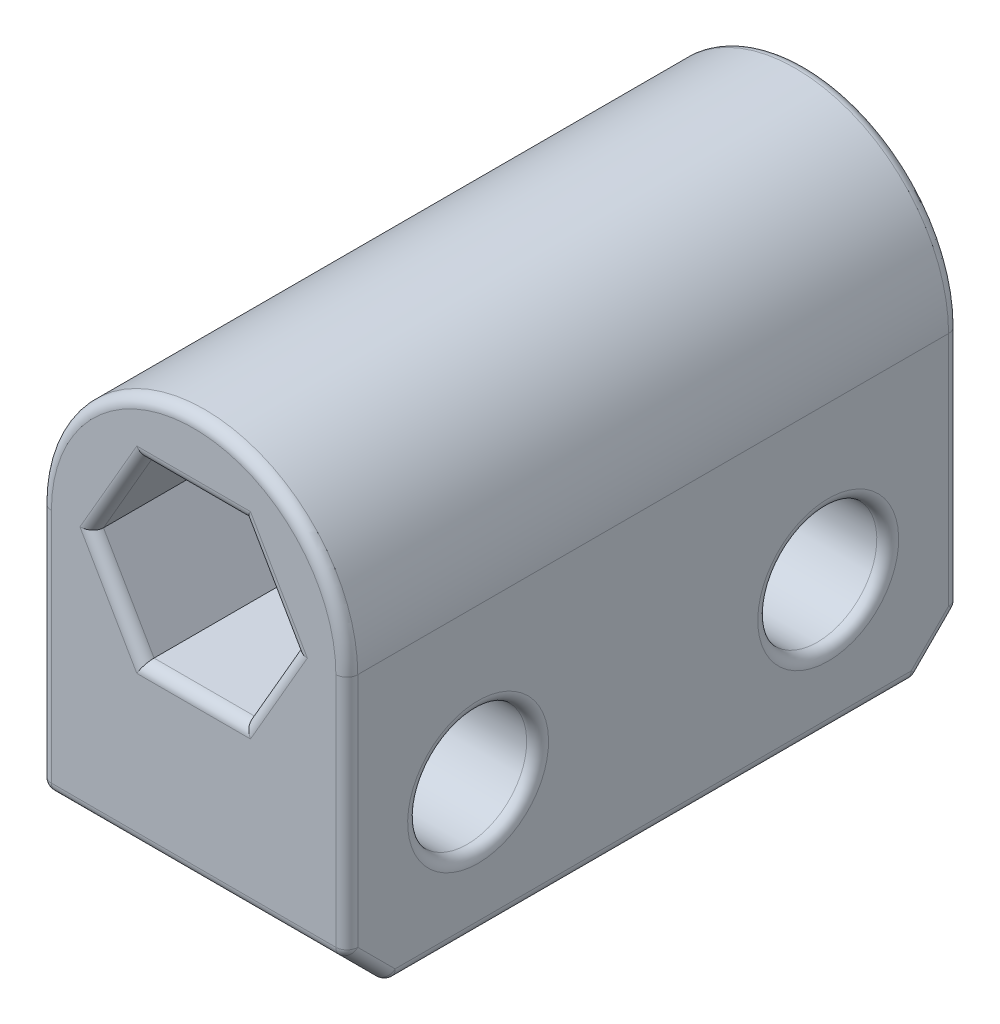
SolidWorks part; units mm, degrees
ref_plane "Front Plane" through (0, 0, 0) normal (0, 0, 1) x (1, 0, 0)
ref_plane "Top Plane" through (0, 0, 0) normal (0, 1, 0) x (1, 0, 0)
ref_plane "Right Plane" through (0, 0, 0) normal (1, 0, 0) x (0, 0, -1)
sketch "Sketch1" plane through (0, 0, 0) normal (0, 0, 1) x (1, 0, 0)
  line L0 (-5.5562, 0) -> (-5.5562, -10.3187)
  line L1 (-5.5562, -10.3187) -> (5.5562, -10.3187)
  line L2 (5.5562, -10.3187) -> (5.5562, 0)
  line L4 (3.6662, 0) -> (1.8331, 3.175)
  line L5 (1.8331, 3.175) -> (-1.8331, 3.175)
  line L6 (-1.8331, 3.175) -> (-3.6662, 0)
  line L7 (-3.6662, 0) -> (-1.8331, -3.175)
  line L8 (-1.8331, -3.175) -> (1.8331, -3.175)
  line L9 (1.8331, -3.175) -> (3.6662, 0)
  arc A1 (-5.5562, 0) -> (5.5562, 0) centre (0, 0) cw
  circle A2 centre (0, 0) radius 3.175 construction
  dimension "D1" = 6.35
  dimension "D2" = 11.1125
  dimension "D3" = 10.3187
extrude "Boss-Extrude1" add sketch "Sketch1" along normal mid plane 22.225
sketch "Sketch2" plane through (-5.5562, 0, 0) normal (-1, 0, 0) x (0, 0, 1)
  line L0 (-6.35, -5.5562) -> (6.35, -5.5562) construction
  circle A0 centre (-6.35, -5.5562) radius 2.159
  circle A1 centre (6.35, -5.5562) radius 2.159
  point P4 (0, -5.5562)
  dimension "D2" = 4.318
  dimension "D3" = 5.5562
  dimension "D1" = 12.7
extrude "Cut-Extrude1" cut sketch "Sketch2" against normal through all
chamfer "Chamfer2" distance 1.5875 angle 45 2 edges at (0, -10.3187, 11.1125) (0, -10.3187, -11.1125)
fillet "Fillet2" radius 0.3969 32 edges at (0, -8.7312, -11.1125) (-5.5562, -9.525, 10.3187) (-5.5562, -9.525, -10.3187) (0, -10.3187, 9.525) (0, -10.3187, -9.525) (5.5562, -9.525, 10.3187) (5.5562, -9.525, -10.3187) (0, -8.7312, 11.1125) (-5.5562, -10.3187, 0) (5.5562, -10.3187, 0) (5.5562, -4.3656, 11.1125) (-5.5562, -4.3656, 11.1125) (0, 5.5562, 11.1125) (5.5562, -4.3656, -11.1125) (-5.5562, -4.3656, -11.1125) (0, 5.5562, -11.1125) (5.5562, -7.7153, -6.35) (-5.5562, -7.7152, -6.35) (-5.5562, -7.7152, 6.35) (5.5562, -7.7153, 6.35) (-2.7496, 1.5875, -11.1125) (0, 3.175, -11.1125) (2.7496, 1.5875, -11.1125) (2.7496, -1.5875, -11.1125) (0, -3.175, -11.1125) (-2.7496, -1.5875, -11.1125) (2.7496, 1.5875, 11.1125) (2.7496, -1.5875, 11.1125) (-2.7496, -1.5875, 11.1125) (-2.7496, 1.5875, 11.1125) (0, 3.175, 11.1125) (0, -3.175, 11.1125)
